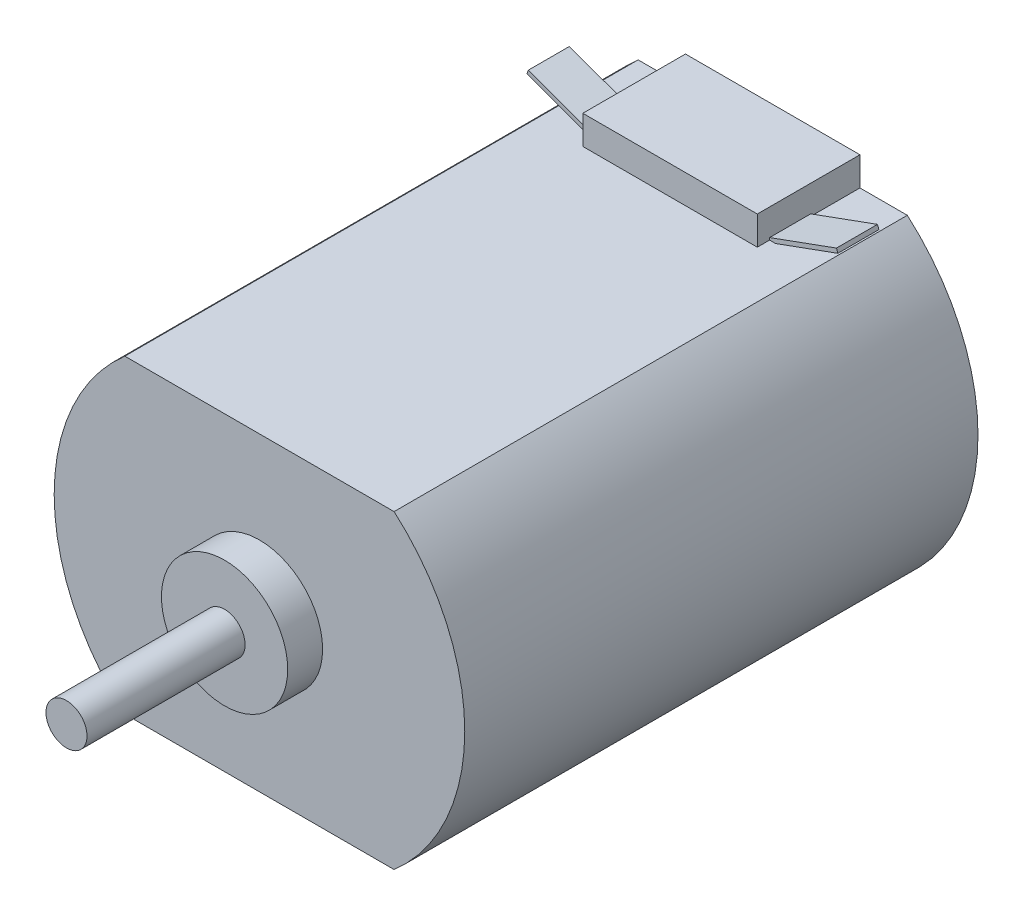
SolidWorks part; units mm, degrees
ref_plane "前视基准面" through (0, 0, 0) normal (0, 0, 1) x (1, 0, 0)
ref_plane "上视基准面" through (0, 0, 0) normal (0, 1, 0) x (1, 0, 0)
ref_plane "右视基准面" through (0, 0, 0) normal (1, 0, 0) x (0, 0, -1)
sketch "草图2" plane through (0, 0, 0) normal (0, 0, 1) x (1, 0, 0)
  line L1 (-6.5572, -7.55) -> (6.5572, -7.55)
  line L3 (-6.5572, 7.55) -> (6.5572, 7.55)
  line L5 (-9.1854, -3.9534) -> (9.1854, 3.9534) construction
  line L6 (-9.1854, 3.9534) -> (9.1854, -3.9534) construction
  arc A0 (6.5572, -7.55) -> (6.5572, 7.55) centre (0, 0) ccw
  arc A1 (-6.5572, 7.55) -> (-6.5572, -7.55) centre (0, 0) ccw
  dimension "D2" = 20
  dimension "D1" = 15.1
extrude "凸台-拉伸1" add sketch "草图2" along normal blind 25
sketch "草图3" plane through (0, 0, 25) normal (0, 0, 1) x (1, 0, 0)
  circle A0 centre (0, 0) radius 1
  dimension "D1" = 2
extrude "凸台-拉伸2" add sketch "草图3" along normal blind 9.4
sketch "草图4" plane through (0, 0, 25) normal (0, 0, 1) x (1, 0, 0)
  circle A0 centre (0, 0) radius 3.075
  dimension "D1" = 6.15
extrude "凸台-拉伸3" add sketch "草图4" along normal blind 1.7
sketch "草图5" plane through (0, 0, 0) normal (0, 0, -1) x (-1, 0, 0)
  line L0 (-3.521, -3.55) -> (3.521, -3.55)
  line L1 (6.5572, -7.55) -> (-6.5572, -7.55) construction
  arc A0 (3.521, -3.55) -> (-3.521, -3.55) centre (0, 0) ccw
  dimension "D1" = 10
  dimension "D2" = 4
extrude "凸台-拉伸4" add sketch "草图5" along normal blind 2.3
sketch "草图6" plane through (0, 0, -2.3) normal (0, 0, -1) x (-1, 0, 0)
  circle A0 centre (0, 0) radius 1
  dimension "D1" = 2
extrude "凸台-拉伸5" add sketch "草图6" along normal blind 1.3
sketch "草图8" plane through (0, 7.55, 0) normal (0, 1, 0) x (1, 0, 0)
  line L0 (6.5572, 0) -> (-6.5572, 0) construction
  line L1 (4.25, -5) -> (-4.25, -5)
  line L2 (4.25, -5) -> (4.25, 0)
  line L3 (4.25, 0) -> (-4.25, 0)
  line L4 (-4.25, -5) -> (-4.25, 0)
  line L5 (4.25, -5) -> (-4.25, 0) construction
  line L6 (4.25, 0) -> (-4.25, -5) construction
  point P0 (0, -2.5)
  point P7 (0, 0)
  point P8 (-0.1801, 0)
  point P9 (0, 0)
  point P10 (0, -2.5)
  point P11 (0, -2.5)
  point P12 (0, 0)
  dimension "D1" = 5
  dimension "D2" = 8.5
extrude "凸台-拉伸6" add sketch "草图8" along normal blind 1.4
ref_plane "基准面1" through (-1.9294, 5.3009, 0) normal (-0.342, 0.9397, 0) x (0, 0, -1)
sketch "草图9" plane through (-1.9294, 5.3009, 0) normal (-0.342, 0.9397, 0) x (0, 0, -1)
  line L0 (-5, -6.5759) -> (0, -6.5759) construction
  line L1 (-2.4, -6.5759) -> (-4.4, -6.5759)
  line L2 (-2.4, -6.5759) -> (-2.4, -10.0759)
  line L3 (-2.4, -10.0759) -> (-4.4, -10.0759)
  line L4 (-4.4, -6.5759) -> (-4.4, -10.0759)
  line L5 (-2.4, -6.5759) -> (-4.4, -10.0759) construction
  line L6 (-2.4, -10.0759) -> (-4.4, -6.5759) construction
  line L7 (0, -8.744) -> (0, -6.5759) construction
  point P0 (-3.4, -8.3259)
  dimension "D1" = 3.5
  dimension "D2" = 2
  dimension "D3" = 3.4
extrude "凸台-拉伸7" add sketch "草图9" along normal mid plane 0.2
mirror "镜向1" about plane through (0, 0, 0) normal (1, 0, 0) of "凸台-拉伸7"
